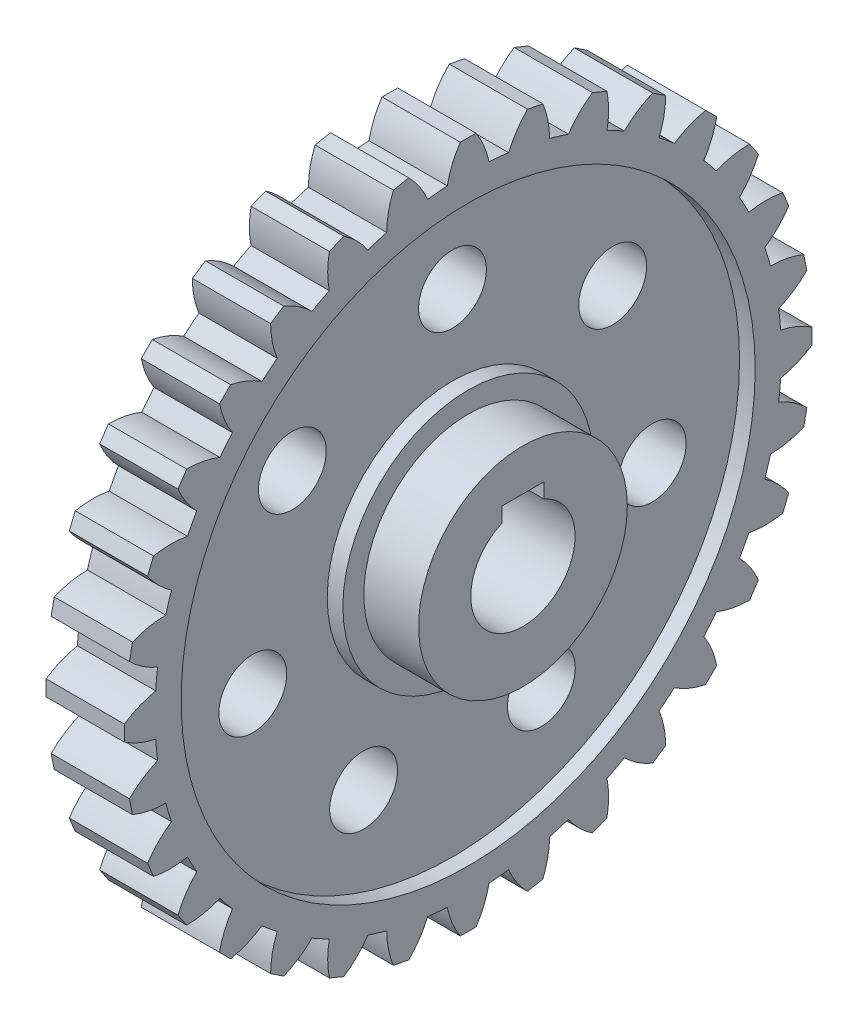
SolidWorks part; units mm, degrees
material "AISI 4130 Steel, normalized at 870C"
ref_plane "Front Plane" through (0, 0, 0) normal (0, 0, 1) x (1, 0, 0)
ref_plane "Top Plane" through (0, 0, 0) normal (0, 1, 0) x (1, 0, 0)
ref_plane "Right Plane" through (0, 0, 0) normal (1, 0, 0) x (0, 0, -1)
sketch "Sketch1" plane through (0, 0, 0) normal (1, 0, 0) x (0, 0, -1)
  circle A0 centre (0, 0) radius 60
  dimension "D1" = 120
extrude "Boss-Extrude1" add sketch "Sketch1" along normal mid plane 15
sketch "Sketch2" plane through (7.5, 0, 0) normal (1, 0, 0) x (0, 0, -1)
  line L0 (0, 0) -> (0, 65.8665) construction
  line L1 (-1.5, 65.8665) -> (1.5, 65.8665)
  arc A0 (-4, 59.8665) -> (4, 59.8665) centre (0, 0) cw
  circle A1 centre (0, 0) radius 60 construction
  arc A2 (1.5, 65.8665) -> (4, 59.8665) centre (-12.6529, 56.4487) cw
  arc A3 (-1.5, 65.8665) -> (-4, 59.8665) centre (12.6529, 56.4487) ccw
  dimension "D4" = 17
  dimension "D1" = 3
  dimension "D2" = 6
  dimension "D3" = 4
extrude "Boss-Extrude2" add sketch "Sketch2" against normal up to surface (15 mm away) up to face at (-7.5, 0, -60)
pattern_circular "CirPattern1" count 32 over 360 about axis through (0, 0, 0) along (1, 0, 0) of "Boss-Extrude2"
sketch "Sketch7" plane through (0, 0, 0) normal (1, 0, 0) x (0, 0, -1)
  circle A0 centre (0, 0) radius 20
  dimension "D1" = 40
extrude "Boss-Extrude5" add sketch "Sketch7" along normal mid plane 36
sketch "Sketch8" plane through (18, 0, 0) normal (1, 0, 0) x (0, 0, -1)
  line L0 (0, 0) -> (0, 12) construction
  line L1 (-4, 12) -> (4, 12)
  line L2 (-4, 12) -> (-4, 9.1652)
  line L3 (4, 12) -> (4, 9.1652)
  arc A0 (-4, 9.1652) -> (4, 9.1652) centre (0, 0) ccw
  dimension "D1" = 20
  dimension "D2" = 8
  dimension "D3" = 12
extrude "Cut-Extrude4" cut sketch "Sketch8" against normal through all
sketch "Sketch9" plane through (7.5, 0, 0) normal (1, 0, 0) x (0, 0, -1)
  circle A0 centre (0, 0) radius 55
  circle A1 centre (0, 0) radius 24
  dimension "D1" = 110
  dimension "D2" = 48
extrude "Cut-Extrude5" cut sketch "Sketch9" against normal blind 3
sketch "Sketch10" plane through (4.5, 0, 0) normal (1, 0, 0) x (0, 0, -1)
  circle A0 centre (0, 0) radius 39.25 construction
  circle A1 centre (0, 39.25) radius 6.5
  circle A2 centre (30.6869, 24.472) radius 6.5
  circle A3 centre (38.2659, -8.7339) radius 6.5
  circle A4 centre (17.0299, -35.363) radius 6.5
  circle A5 centre (-17.0299, -35.363) radius 6.5
  circle A6 centre (-38.2659, -8.7339) radius 6.5
  circle A7 centre (-30.6869, 24.472) radius 6.5
  point P19 (0, 0)
  dimension "D1" = 78.5
  dimension "D2" = 13
  dimension "D3" = 7
extrude "Cut-Extrude6" cut sketch "Sketch10" against normal through all
